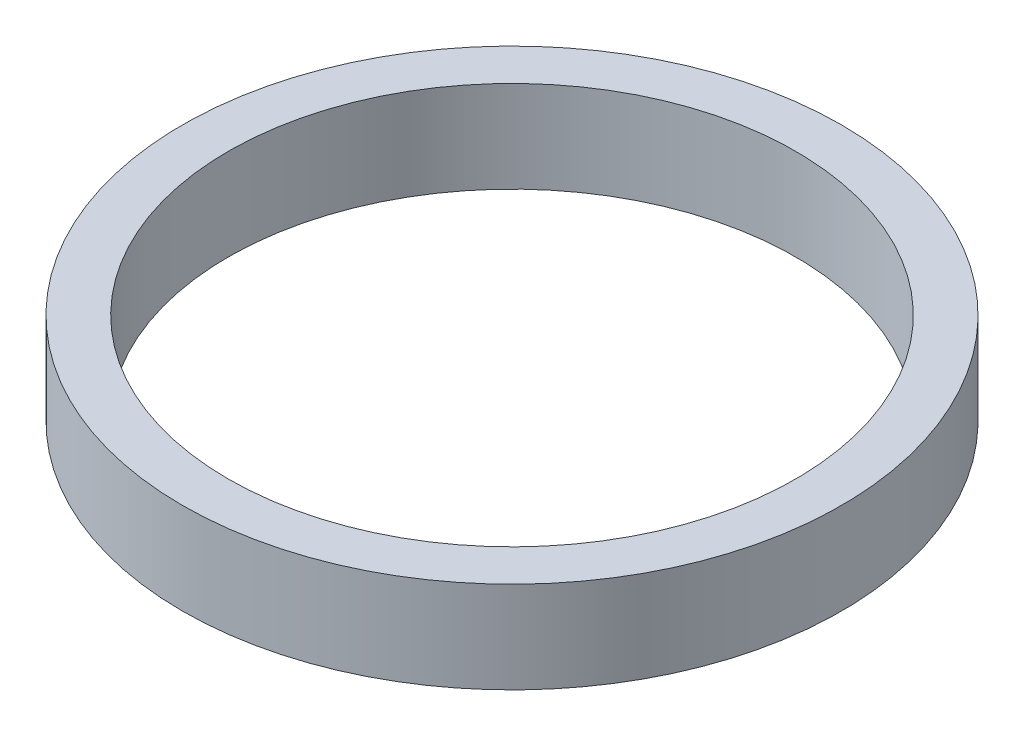
SolidWorks part; units mm, degrees
ref_plane "前基準面" through (0, 0, 0) normal (0, 0, 1) x (1, 0, 0)
ref_plane "上基準面" through (0, 0, 0) normal (0, 1, 0) x (1, 0, 0)
ref_plane "右基準面" through (0, 0, 0) normal (1, 0, 0) x (0, 0, -1)
sketch "草圖1" plane through (0, 0, 0) normal (0, 1, 0) x (1, 0, 0)
  circle A0 centre (0, 0) radius 36
  dimension "D1" = 72
extrude "填料-伸長1" add sketch "草圖1" along normal blind 10
sketch "草圖2" plane through (0, 10, 0) normal (0, 1, 0) x (1, 0, 0)
  circle A0 centre (0, 0) radius 31
  dimension "D1" = 62
extrude "除料-伸長1" cut sketch "草圖2" against normal blind 30
